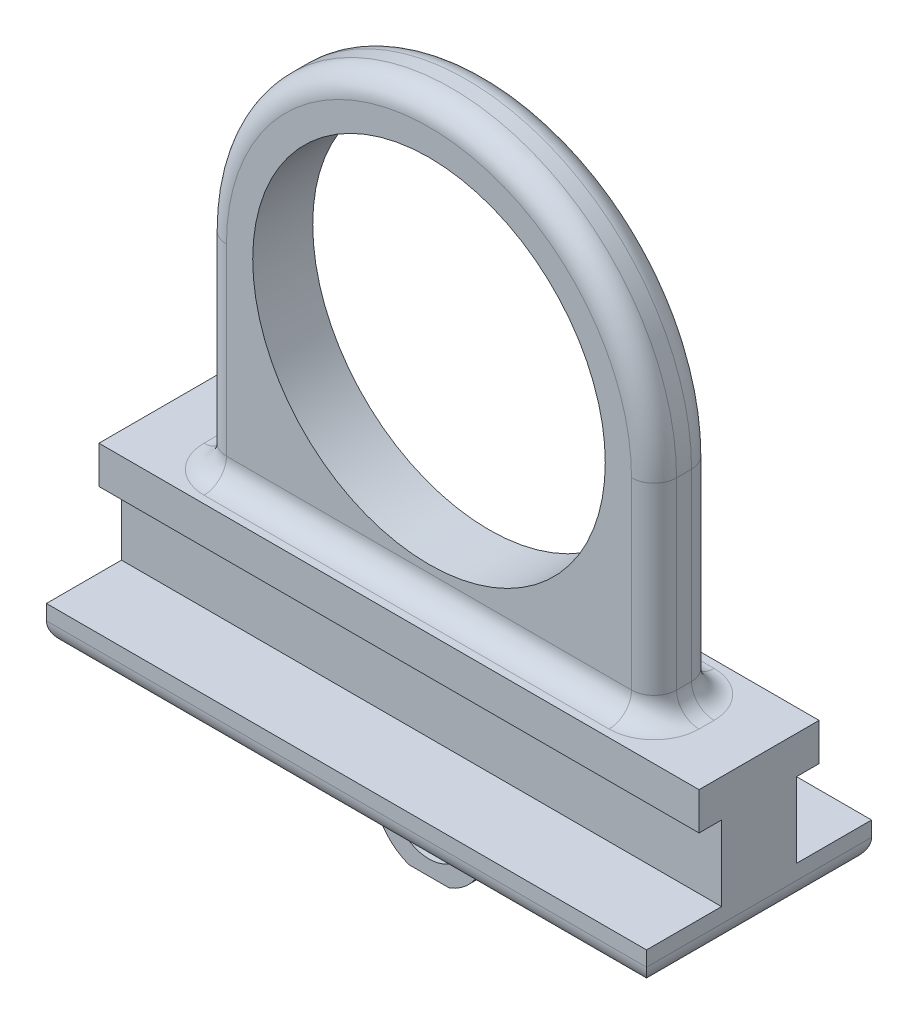
SolidWorks part; units mm, degrees
ref_plane "前视基准面" through (0, 0, 0) normal (0, 0, 1) x (1, 0, 0)
ref_plane "上视基准面" through (0, 0, 0) normal (0, 1, 0) x (1, 0, 0)
ref_plane "右视基准面" through (0, 0, 0) normal (1, 0, 0) x (0, 0, -1)
sketch "草图1" plane through (0, 0, 0) normal (0, 0, 1) x (1, 0, 0)
  line L0 (30, -32.5) -> (-30, -32.5)
  line L1 (-30, 0) -> (-30, -32.5)
  line L2 (30, 0) -> (30, -32.5)
  circle A0 centre (0, 0) radius 23.5
  arc A1 (30, 0) -> (-30, 0) centre (0, 0) ccw
  dimension "D1" = 32.5
extrude "凸台-拉伸1" add sketch "草图1" along normal blind 8
sketch "草图2" plane through (30, 0, 0) normal (1, 0, 0) x (0, 0, -1)
  line L0 (-4, -32.5) -> (-4, -23.7937) construction
  line L1 (1, -32.5) -> (4, -32.5)
  line L2 (4, -32.5) -> (4, -27.5)
  line L3 (4, -27.5) -> (-12, -27.5)
  line L4 (-12, -27.5) -> (-12, -32.5)
  line L5 (-12, -32.5) -> (-9, -32.5)
  line L6 (-9, -32.5) -> (-9, -42.5)
  line L7 (-9, -42.5) -> (-19, -42.5)
  line L8 (-19, -42.5) -> (-19, -47.5)
  line L9 (-19, -47.5) -> (11, -47.5)
  line L10 (11, -47.5) -> (11, -42.5)
  line L11 (11, -42.5) -> (1, -42.5)
  line L12 (1, -42.5) -> (1, -32.5)
  line L13 (-8, -32.5) -> (0, -32.5) construction
  point P18 (-4, -27.5)
  dimension "D1" = 5
  dimension "D3" = 4
  dimension "D4" = 10
  dimension "D5" = 10
  dimension "D6" = 10
  dimension "D7" = 10
  dimension "D8" = 5
  dimension "D9" = 1
  dimension "D10" = 10
extrude "凸台-拉伸2" add sketch "草图2" against normal blind 70
ref_plane "基准面4" through (0, 0, 0) normal (-1, 0, 0) x (0, 0, 1)
mirror "镜向1" about plane through (0, 0, 0) normal (-1, 0, 0) of "凸台-拉伸2"
fillet "圆角1" radius 3 10 edges at (30, -27.5, 4) (-30, -27.5, 4) (0, -27.5, 8) (0, -27.5, 0) (30, -13.75, 8) (0, 30, 8) (30, -13.75, 0) (0, 30, 0) (-30, -13.75, 8) (-30, -13.75, 0)
fillet "圆角2" radius 3 4 edges at (0, -47.5, -11) (-40, -47.5, 4) (0, -47.5, 19) (40, -47.5, 4)
ref_plane "基准面5" through (0, 0, 4) normal (0, 0, 1) x (1, 0, 0)
sketch "草图4" plane through (0, 0, 4) normal (0, 0, 1) x (1, 0, 0)
  line L0 (0, -39.2414) -> (0, -90.726) construction
  line L1 (37, -47.5) -> (-43.3198, -47.5) construction
  line L4 (5, -47.5) -> (5, -52.5)
  line L6 (-5, -47.5) -> (-5, -52.5)
  line L7 (7.5, -47.5) -> (-7.5, -47.5)
  line L8 (7.5, -47.5) -> (7.5, -52.5)
  line L9 (2.6926, -59.5) -> (-2.6926, -59.5)
  line L10 (-7.5, -47.5) -> (-7.5, -52.5)
  arc A0 (-5, -52.5) -> (5, -52.5) centre (0, -52.5) ccw
  arc A1 (2.6926, -59.5) -> (7.5, -52.5) centre (0, -52.5) ccw
  arc A2 (-7.5, -52.5) -> (-2.6926, -59.5) centre (0, -52.5) ccw
extrude "凸台-拉伸3" add sketch "草图4" along normal mid plane 8
